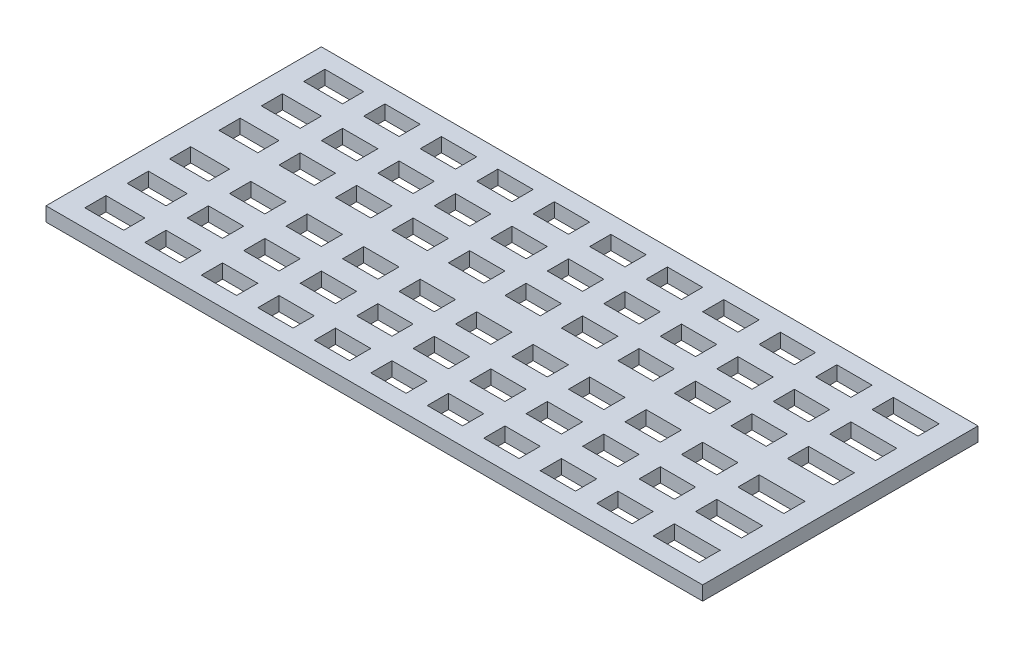
SolidWorks part; units mm, degrees
ref_plane "Front Plane" through (0, 0, 0) normal (0, 0, 1) x (1, 0, 0)
ref_plane "Top Plane" through (0, 0, 0) normal (0, 1, 0) x (1, 0, 0)
ref_plane "Right Plane" through (0, 0, 0) normal (1, 0, 0) x (0, 0, -1)
sketch "Sketch1" plane through (0, 0, 0) normal (0, 1, 0) x (1, 0, 0)
  line L1 (23.25, -9.75) -> (-23.25, -9.75)
  line L2 (23.25, -9.75) -> (23.25, 9.75)
  line L3 (23.25, 9.75) -> (-23.25, 9.75)
  line L4 (-23.25, -9.75) -> (-23.25, 9.75)
  line L5 (23.25, -9.75) -> (-23.25, 9.75) construction
  line L6 (23.25, 9.75) -> (-23.25, -9.75) construction
  point P0 (0, 0)
  dimension "D1" = 46.5
  dimension "D2" = 19.5
extrude "Boss-Extrude1" add sketch "Sketch1" along normal blind 1
sketch "Sketch2" plane through (0, 1, 0) normal (0, 1, 0) x (1, 0, 0)
  line L0 (-23.25, 9.75) -> (-23.25, -9.75) construction
  line L1 (-21.75, 8.5) -> (21.75, 8.5)
  line L2 (-21.75, 8.5) -> (-21.75, 7)
  line L3 (-21.75, 7) -> (21.75, 7)
  line L4 (21.75, 8.5) -> (21.75, 7)
  line L5 (23.25, -9.75) -> (23.25, 9.75) construction
  line L6 (23.25, 9.75) -> (-23.25, 9.75) construction
  line L7 (-23.25, 0) -> (0, 0) construction
  line L8 (-23.25, 6.25) -> (-19.1971, 6.25) construction
  line L9 (21.75, 4) -> (21.75, 5.5)
  line L10 (-21.75, 4) -> (21.75, 4)
  line L11 (-21.75, 5.5) -> (21.75, 5.5)
  line L12 (-21.75, 4) -> (-21.75, 5.5)
  line L13 (-23.25, 3.25) -> (-21.1708, 3.25) construction
  line L14 (21.75, 2.5) -> (21.75, 1)
  line L15 (-21.75, 1) -> (21.75, 1)
  line L16 (-21.75, 2.5) -> (21.75, 2.5)
  line L17 (-21.75, 2.5) -> (-21.75, 1)
  line L18 (21.75, -2.5) -> (21.75, -1)
  line L19 (21.75, -4) -> (21.75, -5.5)
  line L20 (21.75, -8.5) -> (21.75, -7)
  line L21 (-21.75, -1) -> (21.75, -1)
  line L22 (-21.75, -8.5) -> (21.75, -8.5)
  line L23 (-21.75, -7) -> (21.75, -7)
  line L24 (-21.75, -5.5) -> (21.75, -5.5)
  line L25 (-21.75, -4) -> (21.75, -4)
  line L26 (-21.75, -2.5) -> (21.75, -2.5)
  line L27 (-21.75, -2.5) -> (-21.75, -1)
  line L28 (-21.75, -4) -> (-21.75, -5.5)
  line L29 (-21.75, -8.5) -> (-21.75, -7)
  dimension "D1" = 1.5
  dimension "D2" = 1.5
  dimension "D3" = 1.25
  dimension "D4" = 1.5
  dimension "D5" = 0.75
  dimension "D6" = 0.75
extrude "Cut-Extrude1" cut sketch "Sketch2" against normal up to surface (1 mm away) up to face at (0, 0, 0)
sketch "Sketch3" plane through (0, 1, 0) normal (0, 1, 0) x (1, 0, 0)
  line L0 (21.75, 8.5) -> (-21.75, 8.5) construction
  line L1 (-19, 8.5) -> (-17.5, 8.5)
  line L2 (-19, 8.5) -> (-19, -8.5)
  line L3 (-19, -8.5) -> (-17.5, -8.5)
  line L4 (-17.5, 8.5) -> (-17.5, -8.5)
  line L5 (-21.75, -8.5) -> (21.75, -8.5) construction
  line L6 (-15, 8.5) -> (-15, -8.5)
  line L7 (-13.5, 8.5) -> (-13.5, -8.5)
  line L8 (-15, 8.5) -> (-13.5, 8.5)
  line L9 (-15, -8.5) -> (-13.5, -8.5)
  line L10 (-11, 8.5) -> (-11, -8.5)
  line L11 (-9.5, 8.5) -> (-9.5, -8.5)
  line L12 (-11, 8.5) -> (-9.5, 8.5)
  line L13 (-11, -8.5) -> (-9.5, -8.5)
  line L14 (-7, 8.5) -> (-7, -8.5)
  line L15 (-5.5, 8.5) -> (-5.5, -8.5)
  line L16 (-7, 8.5) -> (-5.5, 8.5)
  line L17 (-7, -8.5) -> (-5.5, -8.5)
  line L18 (-3, 8.5) -> (-3, -8.5)
  line L19 (-1.5, 8.5) -> (-1.5, -8.5)
  line L20 (-3, 8.5) -> (-1.5, 8.5)
  line L21 (-3, -8.5) -> (-1.5, -8.5)
  line L22 (1, 8.5) -> (1, -8.5)
  line L23 (2.5, 8.5) -> (2.5, -8.5)
  line L24 (1, 8.5) -> (2.5, 8.5)
  line L25 (1, -8.5) -> (2.5, -8.5)
  line L26 (5, 8.5) -> (5, -8.5)
  line L27 (6.5, 8.5) -> (6.5, -8.5)
  line L28 (5, 8.5) -> (6.5, 8.5)
  line L29 (5, -8.5) -> (6.5, -8.5)
  line L30 (9, 8.5) -> (9, -8.5)
  line L31 (10.5, 8.5) -> (10.5, -8.5)
  line L32 (9, 8.5) -> (10.5, 8.5)
  line L33 (9, -8.5) -> (10.5, -8.5)
  line L34 (13, 8.5) -> (13, -8.5)
  line L35 (14.5, 8.5) -> (14.5, -8.5)
  line L36 (13, 8.5) -> (14.5, 8.5)
  line L37 (13, -8.5) -> (14.5, -8.5)
  line L38 (17, 8.5) -> (17, -8.5)
  line L39 (18.5, 8.5) -> (18.5, -8.5)
  line L40 (17, 8.5) -> (18.5, 8.5)
  line L41 (17, -8.5) -> (18.5, -8.5)
  dimension "D1" = 2.75
  dimension "D2" = 1.5
  dimension "D3" = 10
extrude "Boss-Extrude2" add sketch "Sketch3" against normal up to surface (1 mm away) up to face at (0, 0, 7.75)
